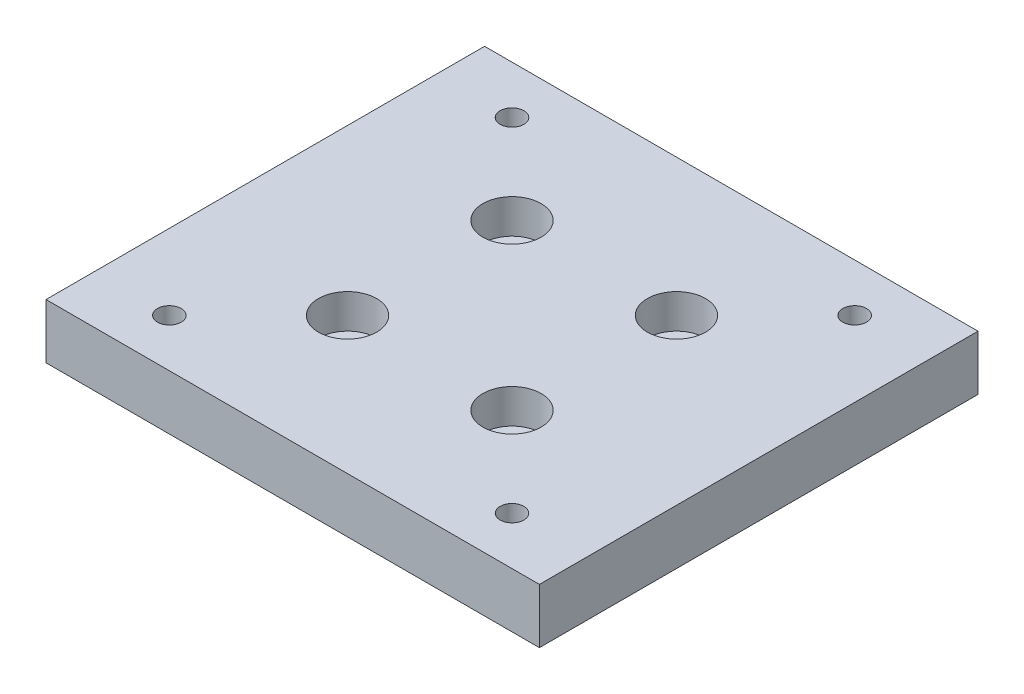
SolidWorks part; units mm, degrees
ref_plane "Front Plane" through (0, 0, 0) normal (0, 0, 1) x (1, 0, 0)
ref_plane "Top Plane" through (0, 0, 0) normal (0, 1, 0) x (1, 0, 0)
ref_plane "Right Plane" through (0, 0, 0) normal (1, 0, 0) x (0, 0, -1)
sketch "Sketch1" plane through (0, 0, 0) normal (0, 1, 0) x (1, 0, 0)
  line L1 (0, 0) -> (114.3, 0)
  line L2 (0, 0) -> (0, 101.6)
  line L3 (0, 101.6) -> (114.3, 101.6)
  line L4 (114.3, 0) -> (114.3, 101.6)
  dimension "D1" = 101.6
  dimension "D2" = 114.3
extrude "Boss-Extrude1" add sketch "Sketch1" along normal blind 12.7
hole_wizard "CBORE for 5/16 Socket Head Cap Screw1" positions "Sketch2" profile "Sketch3" counterbore size "5/16" standard "ANSI Inch" end condition through all
sketch "Sketch2" plane through (0, 12.7, 0) normal (0, 1, 0) x (1, 0, 0)
  line L0 (57.15, 101.6) -> (57.15, 0) construction
  line L1 (114.3, 101.6) -> (0, 101.6) construction
  line L2 (0, 0) -> (114.3, 0) construction
  line L5 (114.3, 50.8) -> (0, 50.8) construction
  line L6 (114.3, 0) -> (114.3, 101.6) construction
  line L7 (0, 101.6) -> (0, 0) construction
  point P0 (38.1, 69.85)
  point P2 (76.2, 69.85)
  point P23 (0, 0)
  point P24 (76.2, 31.75)
  point P25 (38.1, 31.75)
  dimension "D1" = 38.1
  dimension "D2" = 19.05
sketch "Sketch3" plane through (38.1, 12.7, -69.85) normal (1, 0, 0) x (0, 0, 1)
  line L0 (0, 0) -> (0, 12.7)
  line L1 (0, 12.7) -> (4.2164, 12.7)
  line L3 (4.2164, 12.7) -> (4.2164, 7.9375)
  line L4 (4.2164, 7.9375) -> (6.7475, 7.9375)
  line L5 (6.7475, 7.9375) -> (6.7475, 0)
  line L7 (6.7475, 0) -> (0, 0)
  line L11 (0, -6.35) -> (0, 107.95) construction
  dimension "Thru Hole Dia." = 8.4328
  dimension "Thru Hole Depth" = 12.7
  dimension "C'Bore Dia." = 13.495
  dimension "C'Bore Depth" = 7.9375
hole_wizard "M5 Clearance Hole1" positions "Sketch4" profile "Sketch5" hole size "M5" standard "ANSI Metric" end condition through all
sketch "Sketch4" plane through (0, 12.7, 0) normal (0, 1, 0) x (1, 0, 0)
  line L0 (0, 50.8) -> (114.3, 50.8) construction
  line L1 (0, 101.6) -> (0, 0) construction
  line L2 (114.3, 0) -> (114.3, 101.6) construction
  line L5 (57.15, 101.6) -> (57.15, 0) construction
  line L6 (114.3, 101.6) -> (0, 101.6) construction
  line L7 (0, 0) -> (114.3, 0) construction
  point P0 (17.4625, 11.1125)
  point P2 (96.8375, 11.1125)
  point P14 (96.8375, 90.4875)
  point P15 (17.4625, 90.4875)
  point P26 (0, 0)
  dimension "D1" = 79.375
  dimension "D2" = 79.375
sketch "Sketch5" plane through (17.4625, 12.7, -11.1125) normal (1, 0, 0) x (0, 0, 1)
  line L0 (0, 0) -> (0, 12.7)
  line L1 (0, 12.7) -> (2.75, 12.7)
  line L2 (2.75, 12.7) -> (2.75, 0)
  line L5 (2.75, 0) -> (0, 0)
  line L11 (0, -6.35) -> (0, 107.95) construction
  dimension "Thru Hole Dia." = 5.5
  dimension "Thru Hole Depth" = 12.7
